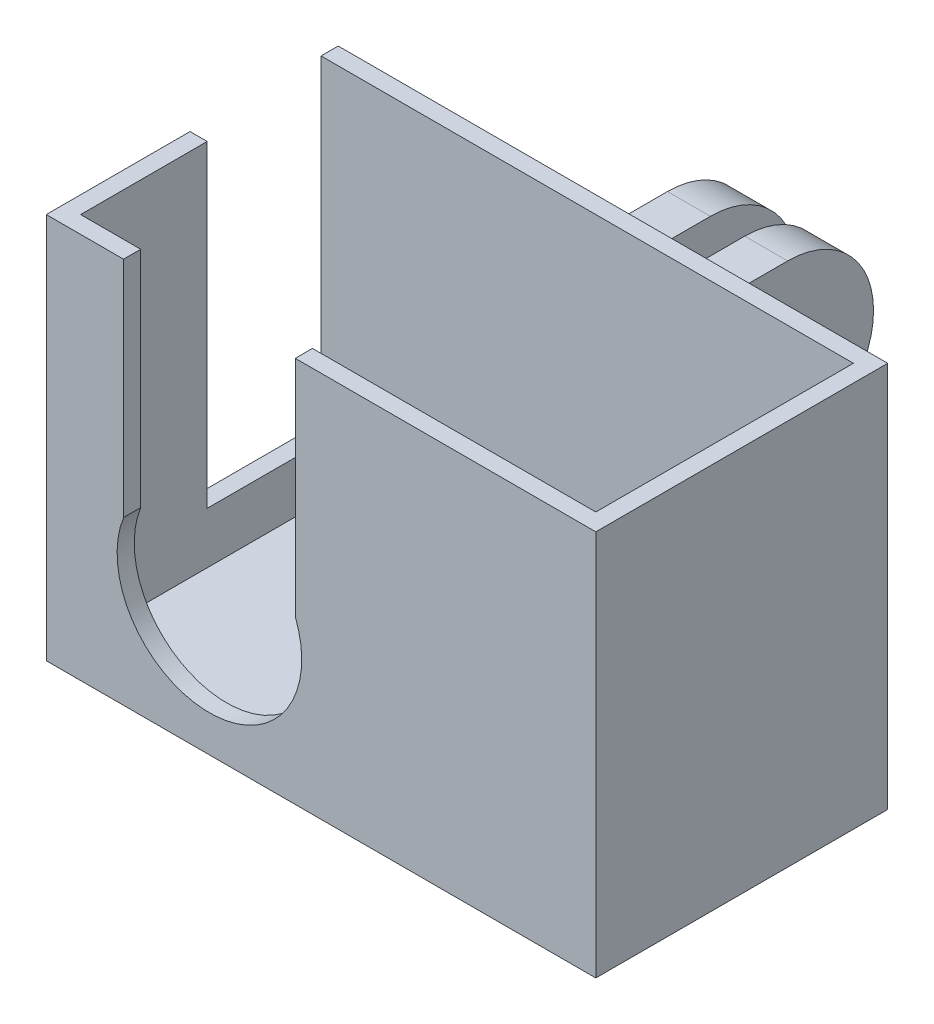
SolidWorks part; units mm, degrees
ref_plane "Front Plane" through (0, 0, 0) normal (0, 0, 1) x (1, 0, 0)
ref_plane "Top Plane" through (0, 0, 0) normal (0, 1, 0) x (1, 0, 0)
ref_plane "Right Plane" through (0, 0, 0) normal (1, 0, 0) x (0, 0, -1)
sketch "Sketch1" plane through (0, 0, 0) normal (0, 0, 1) x (1, 0, 0)
  line L1 (-30.3462, 18.505) -> (33.6538, 18.505)
  line L2 (-30.3462, 18.505) -> (-30.3462, -26.495)
  line L3 (-30.3462, -26.495) -> (33.6538, -26.495)
  line L4 (33.6538, 18.505) -> (33.6538, -26.495)
  dimension "D1" = 64
  dimension "D2" = 45
extrude "Boss-Extrude1" add sketch "Sketch1" along normal blind 34
sketch "Sketch2" plane through (0, 0, 34) normal (0, 0, 1) x (1, 0, 0)
  line L0 (-30.3462, -26.495) -> (33.6538, -26.495) construction
  line L1 (-30.3462, 18.505) -> (-30.3462, -26.495) construction
  circle A0 centre (-11.3462, -11.495) radius 10.75
  dimension "D1" = 15
  dimension "D2" = 21.5
  dimension "D3" = 19
extrude "Cut-Extrude1" cut sketch "Sketch2" against normal blind 6
sketch "Sketch3" plane through (0, 0, 34) normal (0, 0, 1) x (1, 0, 0)
  line L0 (-30.3462, 18.505) -> (-30.3462, -26.495) construction
  line L5 (-28.3462, 16.505) -> (31.6538, 16.505)
  line L6 (-28.3462, 16.505) -> (-28.3462, -24.495)
  line L7 (-28.3462, -24.495) -> (31.6538, -24.495)
  line L8 (31.6538, 16.505) -> (31.6538, -24.495)
  line L9 (33.6538, -26.495) -> (33.6538, 18.505) construction
  line L10 (33.6538, 18.505) -> (-30.3462, 18.505) construction
  line L11 (-30.3462, -26.495) -> (33.6538, -26.495) construction
  dimension "D1" = 2
  dimension "D2" = 2
  dimension "D3" = 2
  dimension "D4" = 2
extrude "Cut-Extrude2" cut sketch "Sketch3" against normal blind 27 from offset 2 offset against normal yes
sketch "Sketch4" plane through (0, 18.505, 0) normal (0, 1, 0) x (1, 0, 0)
  line L0 (-30.3462, -34) -> (-30.3462, 0) construction
  line L1 (-28.3462, -2) -> (31.6538, -2)
  line L2 (-28.3462, -2) -> (-28.3462, -32)
  line L3 (-28.3462, -32) -> (31.6538, -32)
  line L4 (31.6538, -2) -> (31.6538, -32)
  line L5 (33.6538, -34) -> (33.6538, 0) construction
  line L6 (-24.75, 0) -> (24.75, 0) construction
  line L7 (33.6538, -34) -> (-30.3462, -34) construction
  dimension "D1" = 2
  dimension "D2" = 2
  dimension "D3" = 2
  dimension "D4" = 2
extrude "Cut-Extrude3" cut sketch "Sketch4" against normal up to surface (43 mm away) up to face at (1.6538, -24.495, 18.5)
sketch "Sketch5" plane through (0, 18.505, 0) normal (0, 1, 0) x (1, 0, 0)
  line L0 (-28.3462, -32) -> (31.6538, -32) construction
  line L1 (-21.3462, -32) -> (-1.3462, -32)
  line L2 (-21.3462, -32) -> (-21.3462, -34)
  line L3 (-21.3462, -34) -> (-1.3462, -34)
  line L4 (-1.3462, -32) -> (-1.3462, -34)
  line L5 (33.6538, -34) -> (-30.3462, -34) construction
  line L6 (-30.3462, -34) -> (-30.3462, 0) construction
  dimension "D1" = 20
  dimension "D2" = 9
extrude "Cut-Extrude4" cut sketch "Sketch5" against normal blind 27
sketch "Sketch7" plane through (0, 0, 0) normal (1, 0, 0) x (0, 0, -1)
  line L1 (0, 7.9996) -> (15, 7.9996)
  line L2 (0, 7.9996) -> (0, -12.0004)
  line L3 (0, -12.0004) -> (15, -12.0004)
  arc A0 (15, 7.9996) -> (15, -12.0004) centre (15, -2.0004) cw
  dimension "D3" = 10
  dimension "D1" = 15
  dimension "D2" = 20
extrude "Boss-Extrude2" add sketch "Sketch7" along normal blind 5 from offset 2
sketch "Sketch8" plane through (0, 0, 0) normal (1, 0, 0) x (0, 0, -1)
  line L0 (0, -12.0004) -> (0, 7.9996)
  line L1 (0, 7.9996) -> (15, 7.9996)
  line L2 (0, -12.0004) -> (15, -12.0004)
  arc A0 (15, -12.0004) -> (15, 7.9996) centre (15, -2.0004) ccw
  dimension "D4" = 10
  dimension "D1" = 15
  dimension "D2" = 15
  dimension "D3" = 20
extrude "Boss-Extrude3" add sketch "Sketch8" against normal blind 5 from offset 2 offset against normal yes
sketch "Sketch10" plane through (-30.3462, 0, 0) normal (-1, 0, 0) x (0, 0, 1)
  line L2 (2, -18.495) -> (2, 18.505)
  line L3 (2, 18.505) -> (17.2555, 18.505)
  line L5 (34, 18.505) -> (0, 18.505) construction
  line L6 (17.2555, -18.495) -> (17.2555, 18.505)
  line L7 (0, 18.505) -> (0, -26.495) construction
  line L8 (2, -18.495) -> (17.2555, -18.495)
  line L9 (34, -26.495) -> (0, -26.495) construction
  dimension "D1" = 2
  dimension "D2" = 15.2555
  dimension "D3" = 8
extrude "Cut-Extrude5" cut sketch "Sketch10" against normal up to surface (2 mm away) up to face at (-28.3462, -2.995, 17)
